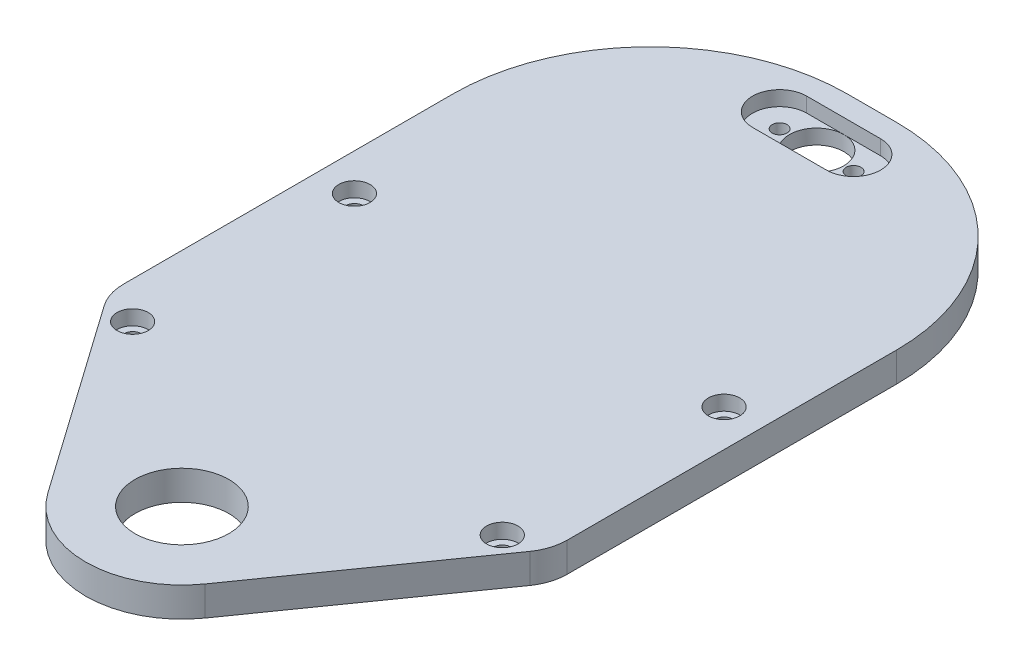
SolidWorks part; units mm, degrees
ref_plane "Front Plane" through (0, 0, 0) normal (0, 0, 1) x (1, 0, 0)
ref_plane "Top Plane" through (0, 0, 0) normal (0, 1, 0) x (1, 0, 0)
ref_plane "Right Plane" through (0, 0, 0) normal (1, 0, 0) x (0, 0, -1)
sketch "Sketch1" plane through (0, 0, 0) normal (0, 1, 0) x (1, 0, 0)
  line L0 (45, -55) -> (15.9651, -96.2401)
  line L2 (-45, -55) -> (-45, 55)
  line L3 (-45, 55) -> (45, 55)
  line L4 (45, -55) -> (45, 55)
  line L5 (-45, -55) -> (45, 55) construction
  line L6 (-45, 55) -> (45, -55) construction
  line L7 (-45, -55) -> (-15.9651, -96.2401)
  circle A0 centre (0, -85) radius 9.525
  arc A1 (-15.9651, -96.2401) -> (15.9651, -96.2401) centre (0, -85) ccw
  point P0 (0, 0)
  dimension "D3" = 19.05
  dimension "D5" = 10
  dimension "D1" = 90
  dimension "D2" = 110
  dimension "D4" = 30
  dimension "D6" = 110
extrude "Body" add sketch "Sketch1" along normal blind 6
sketch "Sketch2" plane through (0, 6, 0) normal (0, 1, 0) x (1, 0, 0)
  line L0 (45, 55) -> (-45, 55) construction
  line L1 (-45, 55) -> (-45, -55) construction
  circle A0 centre (6.2734, 45) radius 1.5
  circle A1 centre (-8.7266, 45) radius 1.5
  circle A2 centre (-1.2266, 45) radius 5.5
  circle A4 centre (37.5, -57.5) radius 1.75
  circle A5 centre (-37.5, -57.5) radius 1.75
  circle A9 centre (-37.5, -12.5) radius 1.75
  circle A11 centre (37.5, -12.5) radius 1.75
  dimension "D4" = 11
  dimension "D7" = 3
  dimension "D8" = 3
  dimension "D11" = 3.5
  dimension "D12" = 3.5
  dimension "D14" = 3.5
  dimension "D15" = 45
  dimension "D16" = 3.5
  dimension "D1" = 10
  dimension "D2" = 0
  dimension "D3" = 0
  dimension "D5" = 7.5
  dimension "D6" = 7.5
  dimension "D9" = 75
  dimension "D10" = 7.5
  dimension "D13" = 112.5
  dimension "D17" = 0
extrude "Holes" cut sketch "Sketch2" against normal up to surface (6 mm away) up to face at (0, 0, 33.4609)
fillet "Fillet1" radius 10 2 edges at (45, 3, 55) (-45, 3, 55)
fillet "Fillet2" radius 40 2 edges at (45, 3, -55) (-45, 3, -55)
sketch "Sketch3" plane through (0, 6, 0) normal (0, 1, 0) x (1, 0, 0)
  line L2 (-8.7266, 50.5) -> (6.2734, 50.5)
  line L3 (6.2734, 39.5) -> (-8.7266, 39.5)
  circle A0 centre (-37.5, -12.5) radius 3.175
  circle A1 centre (37.5, -12.5) radius 3.175
  circle A2 centre (37.5, -57.5) radius 3.175
  circle A3 centre (-37.5, -57.5) radius 3.175
  arc A7 (-8.7266, 50.5) -> (-8.7266, 39.5) centre (-8.7266, 45) ccw
  arc A8 (6.2734, 39.5) -> (6.2734, 50.5) centre (6.2734, 45) ccw
extrude "Cut-Extrude2" cut sketch "Sketch3" against normal offset from surface (3 mm away) 3 up to face at (-8.7266, 0, -43.5)
sketch "Sketch4" plane through (0, 6, 0) normal (0, 1, 0) x (1, 0, 0)
  circle A2 centre (0, -85) radius 5.0564
